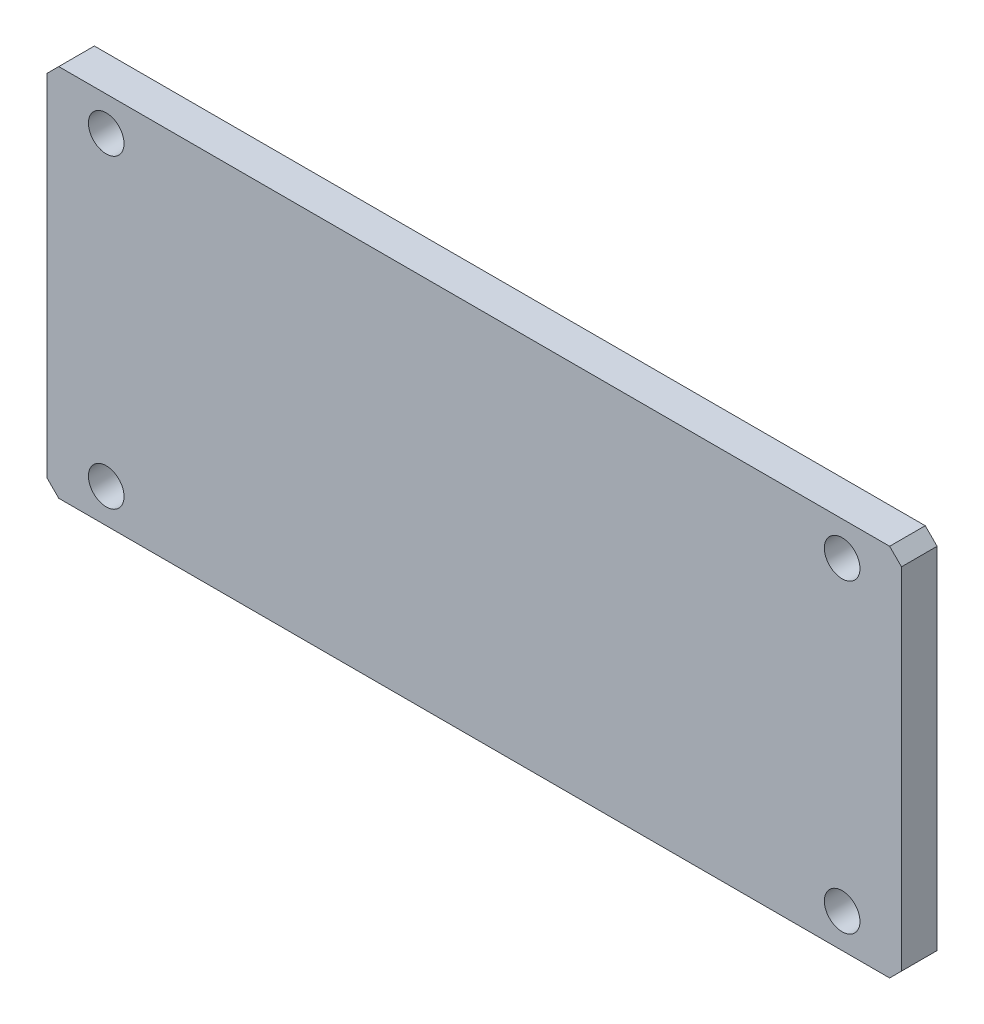
SolidWorks part; units mm, degrees
material "Hexcel AS4C (3000 丝)"
ref_plane "前视基准面" through (0, 0, 0) normal (0, 0, 1) x (1, 0, 0)
ref_plane "上视基准面" through (0, 0, 0) normal (0, 1, 0) x (1, 0, 0)
ref_plane "右视基准面" through (0, 0, 0) normal (1, 0, 0) x (0, 0, -1)
sketch "草图1" plane through (0, 0, -173.2552) normal (0, 0, -1) x (-1, 0, 0)
  line L0 (210.8972, 142.1992) -> (140.8972, 142.1992) construction
  line L1 (140.8972, 110.6992) -> (210.8972, 110.6992)
  line L2 (139.8972, 111.6992) -> (139.8972, 141.1992)
  line L3 (140.8972, 142.1992) -> (210.8972, 142.1992)
  line L4 (211.8972, 111.6992) -> (211.8972, 141.1992)
  line L5 (139.8972, 110.6992) -> (211.8972, 142.1992) construction
  line L6 (139.8972, 142.1992) -> (211.8972, 110.6992) construction
  line L7 (202.8972, 110.6992) -> (210.8972, 110.6992) construction
  line L8 (139.8972, 141.1992) -> (139.8972, 111.6992) construction
  line L9 (211.8972, 111.6992) -> (211.8972, 141.1992) construction
  line L10 (210.8972, 142.1992) -> (211.8972, 141.1992)
  line L11 (210.8972, 110.6992) -> (211.8972, 111.6992)
  line L12 (139.8972, 111.6992) -> (140.8972, 110.6992)
  line L13 (139.8972, 141.1992) -> (140.8972, 142.1992)
  circle A0 centre (206.8972, 139.3242) radius 1.5
  circle A1 centre (206.8972, 113.5742) radius 1.5
  circle A2 centre (144.8972, 113.5742) radius 1.5
  circle A3 centre (144.8972, 139.3242) radius 1.5
  point P0 (175.8972, 126.4492)
extrude "凸台-拉伸1" add sketch "草图1" along normal blind 3
